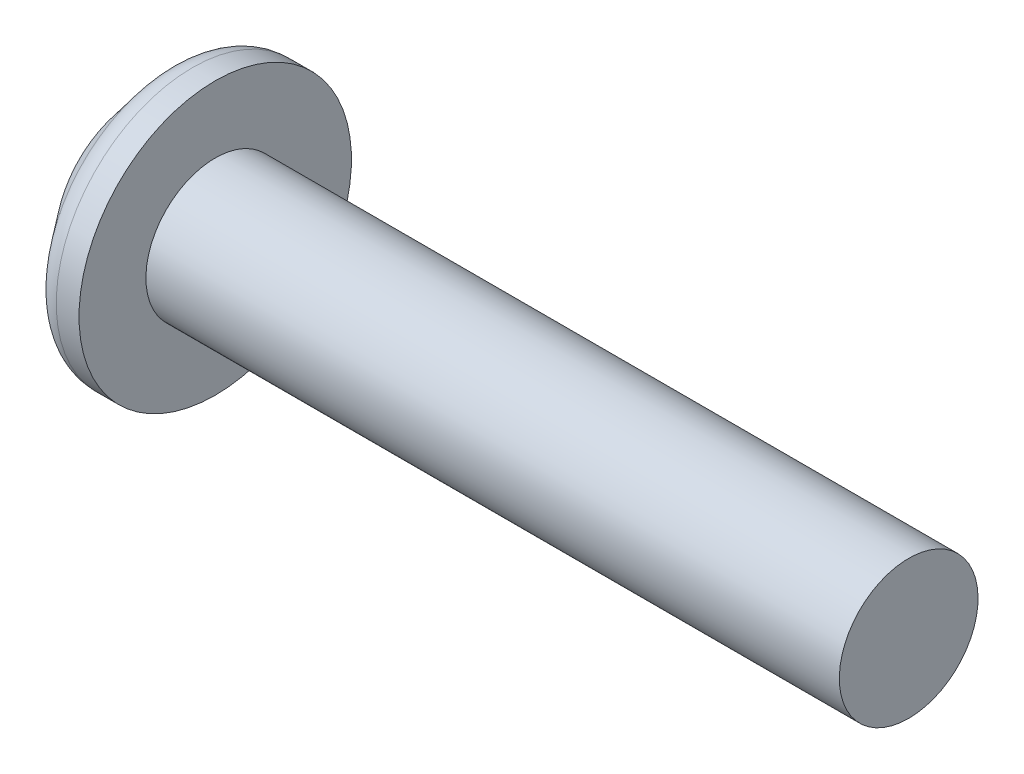
SolidWorks part; units mm, degrees
material "Plain Carbon Steel"
ref_plane "Front Plane" through (0, 0, 0) normal (0, 0, 1) x (1, 0, 0)
ref_plane "Top Plane" through (0, 0, 0) normal (0, 1, 0) x (1, 0, 0)
ref_plane "Right Plane" through (0, 0, 0) normal (1, 0, 0) x (0, 0, -1)
sketch "Sketch1" plane through (0, 0, 0) normal (0, 0, 1) x (1, 0, 0)
  line L0 (0, 0) -> (15.7, 0) construction
  line L1 (15.7, 0) -> (15.7, 1.4)
  line L2 (15.7, 1.4) -> (1.7, 1.4)
  line L3 (1.7, 1.4) -> (1.7, 2.75)
  line L4 (15.7, 0) -> (0, 0)
  line L5 (1, 2.75) -> (1.7, 2.75)
  line L6 (0, 0) -> (0, 1.5)
  line L7 (0, 0) -> (47.315, 0) construction
  line L8 (0, 1.5) -> (1, 2.75)
  dimension "D2" = 5.5
  dimension "D1" = 0.7
  dimension "D3" = 1.7
  dimension "D4" = 3
  dimension "D5" = 14
  dimension "D6" = 2.8
revolve "Revolve1" add sketch "Sketch1" angle 360 about L7
sketch "Sketch2" plane through (0, 0, 0) normal (-1, 0, 0) x (0, 0, 1)
  line L1 (1.1547, 0) -> (0.5774, 1)
  line L2 (0.5774, 1) -> (-0.5774, 1)
  line L3 (-0.5774, 1) -> (-1.1547, 0)
  line L4 (-1.1547, 0) -> (-0.5774, -1)
  line L5 (-0.5774, -1) -> (0.5774, -1)
  line L6 (0.5774, -1) -> (1.1547, 0)
  circle A0 centre (0, 0) radius 1 construction
  dimension "D1" = 2
extrude "Cut-Extrude1" cut sketch "Sketch2" against normal blind 1.5
fillet "Fillet1" radius 0.5 2 edges at (1, -2.75, 0) (0, -1.5, 0)
